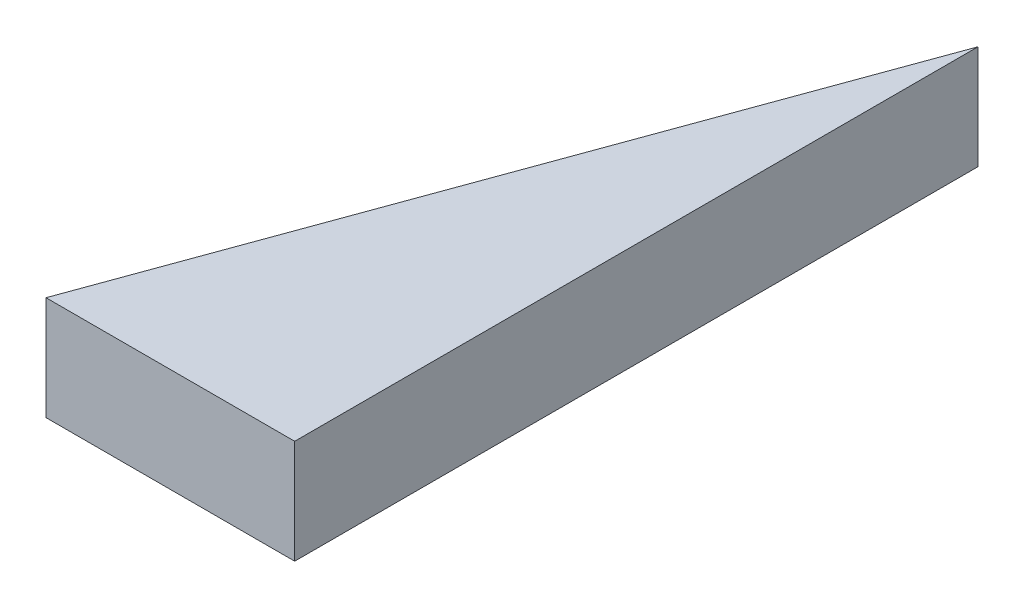
SolidWorks part; units mm, degrees
material "MDF"
ref_plane "Front Plane" through (0, 0, 0) normal (0, 0, 1) x (1, 0, 0)
ref_plane "Top Plane" through (0, 0, 0) normal (0, 1, 0) x (1, 0, 0)
ref_plane "Right Plane" through (0, 0, 0) normal (1, 0, 0) x (0, 0, -1)
sketch "Sketch1" plane through (0, 0, 0) normal (0, 1, 0) x (1, 0, 0)
  line L0 (0, 0) -> (30.4038, 83.5406)
  line L1 (30.4038, 83.5406) -> (30.4038, 0)
  line L2 (-55, 0) -> (55, 0) construction
  line L3 (30.4038, 0) -> (0, 0)
  dimension "D1" = 30.4038
  dimension "D2" = 83.5406
extrude "Boss-Extrude1" add sketch "Sketch1" along normal blind 12.7
